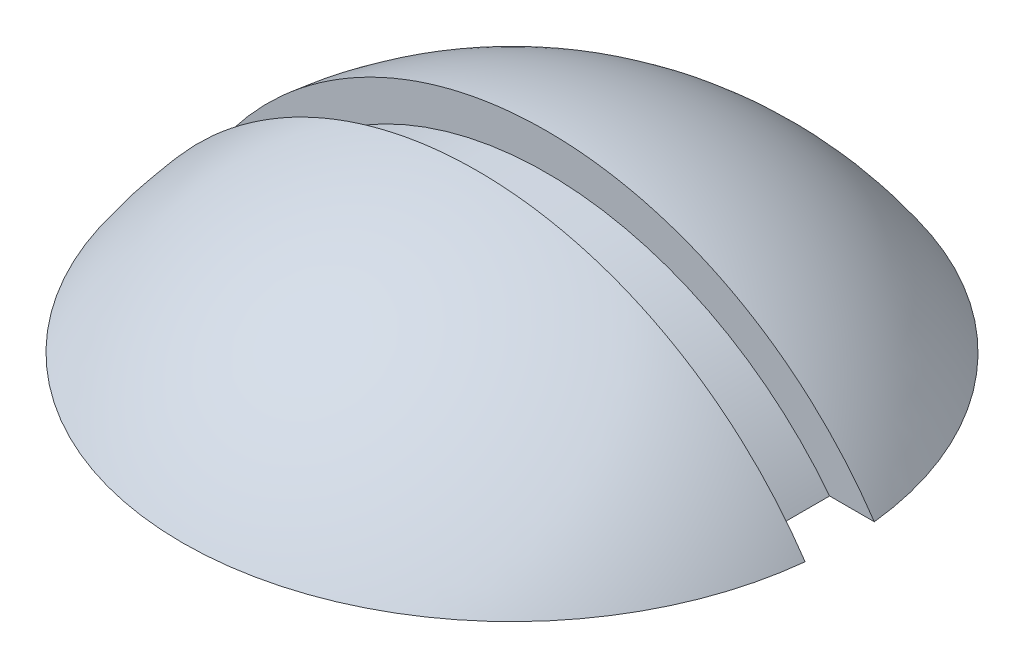
SolidWorks part; units mm, degrees
material "ABS"
ref_plane "Front Plane" through (0, 0, 0) normal (0, 0, 1) x (1, 0, 0)
ref_plane "Top Plane" through (0, 0, 0) normal (0, 1, 0) x (1, 0, 0)
ref_plane "Right Plane" through (0, 0, 0) normal (1, 0, 0) x (0, 0, -1)
sketch "Sketch1" plane through (0, 0, 0) normal (0, 0, 1) x (1, 0, 0)
  line L0 (-57.1359, 44.45) -> (-35.56, 44.45)
  line L1 (0, 57.15) -> (-35.56, 57.15)
  line L4 (-35.56, 57.15) -> (-35.56, 44.45)
  line L5 (0, 57.15) -> (0, 72.39) construction
  line L6 (0, 57.15) -> (0, 72.39)
  line L8 (-57.1359, 44.45) -> (-66.5267, 44.45)
  line L9 (0, 72.39) -> (0, 80.01)
  arc A4 (0, 80.01) -> (-66.5267, 44.45) centre (0, 0) ccw
  dimension "D1" = 44.45
  dimension "D6" = 160.02
  dimension "D2" = 21.5759
  dimension "D3" = 57.1359
  dimension "D4" = 12.7
  dimension "D5" = 35.56
revolve "Revolve3" add sketch "Sketch1" angle 180 about L5
sketch "Sketch4" plane through (0, 0, 0) normal (0, 0, -1) x (-1, 0, 0)
  line L0 (-66.5267, 44.45) -> (-35.56, 44.45) construction
  line L1 (66.5267, 44.45) -> (35.56, 44.45) construction
  line L2 (-66.5267, 44.45) -> (-57.1359, 44.45)
  line L3 (66.5267, 44.45) -> (57.1359, 44.45)
  arc A0 (57.1359, 44.45) -> (-57.1359, 44.45) centre (0, 0) ccw
  arc A1 (66.5267, 44.45) -> (-66.5267, 44.45) centre (0, 0) ccw construction
  arc A2 (66.5267, 44.45) -> (-66.5267, 44.45) centre (0, 0) ccw
  dimension "D1" = 144.78
extrude "Cut-Extrude2" cut sketch "Sketch4" against normal blind 6.985
mirror "Mirror1" of "Cut-Extrude2", "Revolve3"
